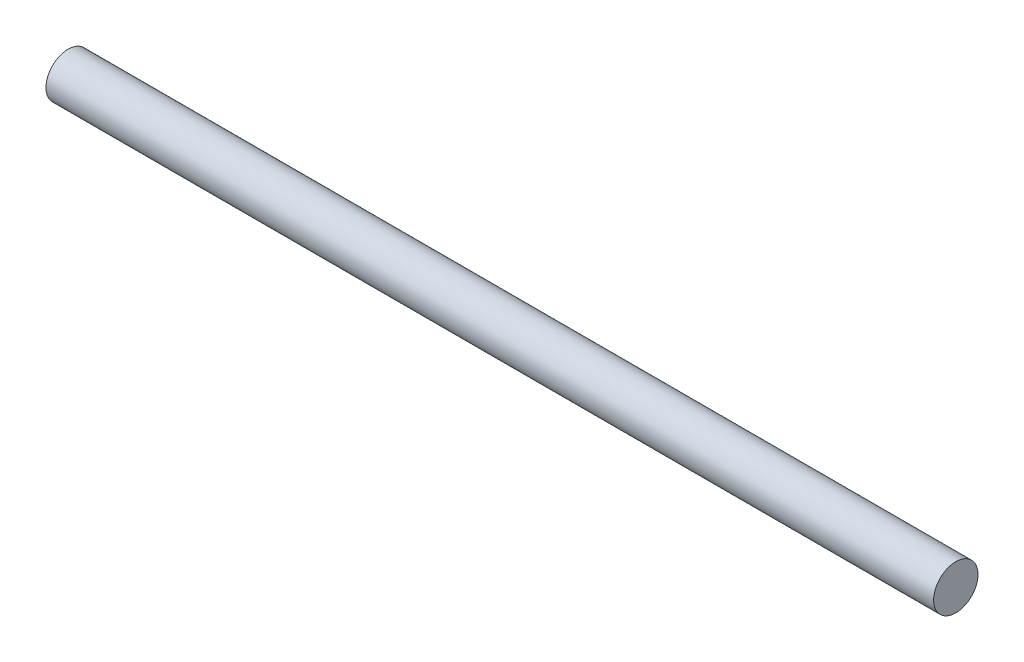
SolidWorks part; units mm, degrees
ref_plane "Front Plane" through (0, 0, 0) normal (1, 0, 0) x (0, 1, 0)
ref_plane "Top Plane" through (0, 0, 0) normal (0, 0, 1) x (0, 1, 0)
ref_plane "Right Plane" through (0, 0, 0) normal (0, 1, 0) x (-1, 0, 0)
sketch "Sketch1" plane through (0, 0, 0) normal (1, 0, 0) x (0, 1, 0)
  circle A0 centre (-2.7043, 2.585) radius 6.35
  dimension "D1" = 12.7
extrude "Boss-Extrude1" add sketch "Sketch1" along normal blind 254 contours A0
